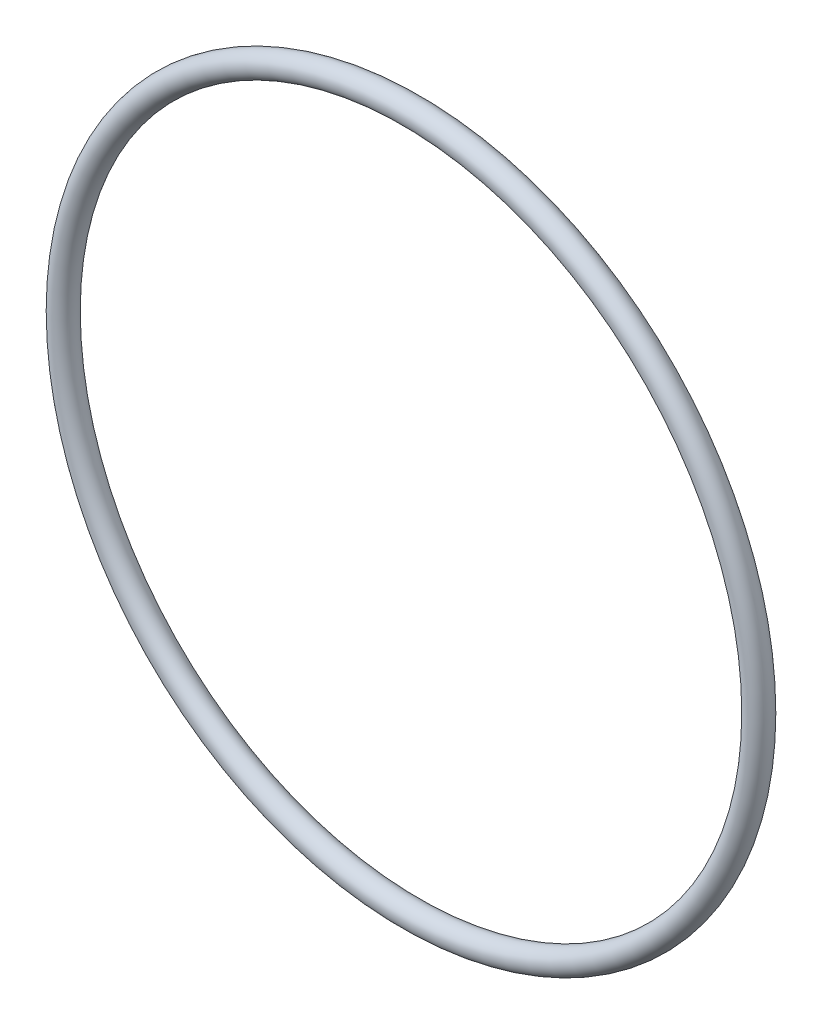
SolidWorks part; units mm, degrees
ref_plane "Front" through (0, 0, 0) normal (0, 0, 1) x (1, 0, 0)
ref_plane "Top" through (0, 0, 0) normal (0, 1, 0) x (1, 0, 0)
ref_plane "Right" through (0, 0, 0) normal (1, 0, 0) x (0, 0, -1)
sketch "Sketch1" plane through (0, 0, 0) normal (1, 0, 0) x (0, -1, 0)
  line L0 (0, -2.667) -> (0, 2.667) construction
  line L2 (-87.5919, 0) -> (87.5919, 0) construction
  line L3 (-74.295, 0) -> (74.295, 0) construction
  circle A0 centre (76.962, 0) radius 2.667
  point P9 (74.295, 0)
  point P10 (79.629, 0)
  point P13 (76.962, 2.667)
  point P14 (76.962, -2.667)
  dimension "Width" = 5.334
  dimension "ID" = 148.59
revolve "Revolve1" add sketch "Sketch1" angle 360 about L0
